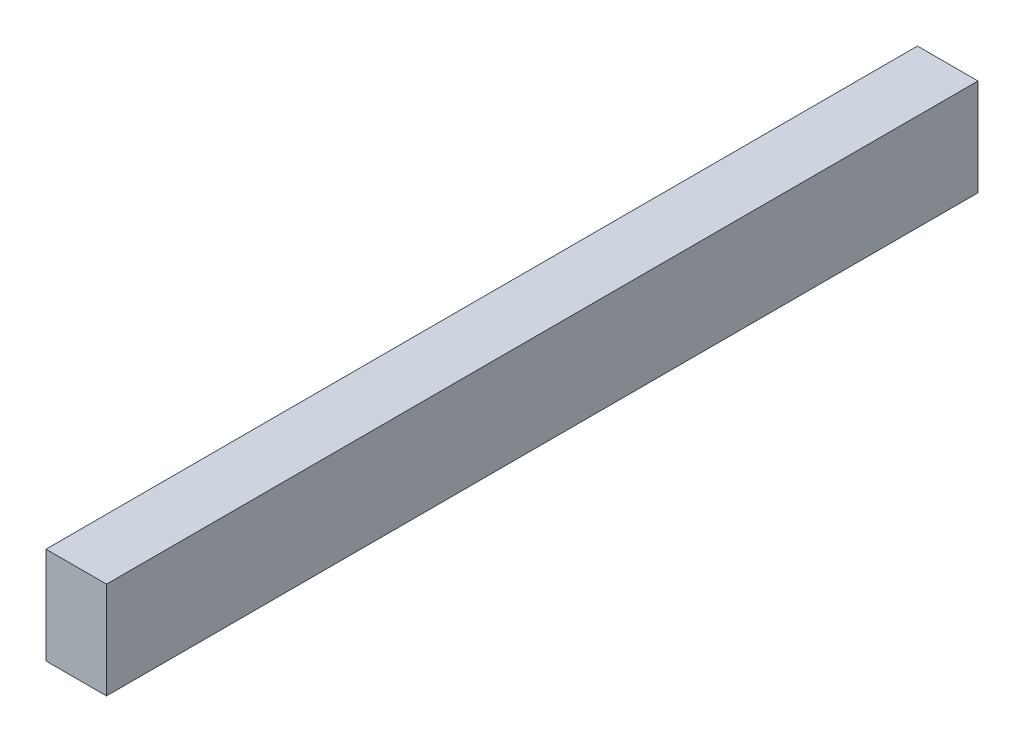
SolidWorks part; units mm, degrees
ref_plane "Plan de face" through (0, 0, 0) normal (0, 0, 1) x (1, 0, 0)
ref_plane "Plan de dessus" through (0, 0, 0) normal (0, 1, 0) x (1, 0, 0)
ref_plane "Plan de droite" through (0, 0, 0) normal (1, 0, 0) x (0, 0, -1)
sketch "Esquisse1" plane through (0, 0, 0) normal (0, 0, 1) x (1, 0, 0)
  line L9 (0, 0) -> (25, 0)
  line L10 (0, 0) -> (0, 40)
  line L11 (0, 40) -> (25, 40)
  line L12 (25, 0) -> (25, 40)
  dimension "D1" = 25
  dimension "D2" = 40
extrude "Boss.-Extru.1" add sketch "Esquisse1" along normal blind 360
